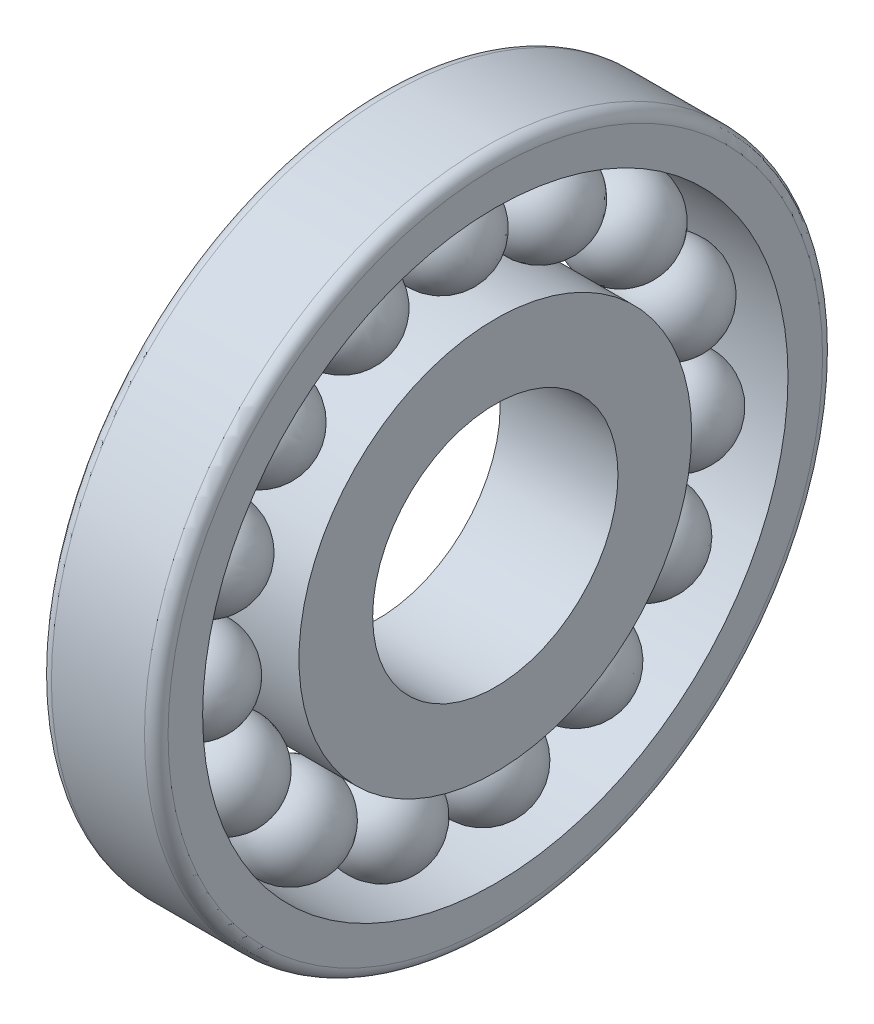
SolidWorks part; units mm, degrees
ref_plane "Front Plane" through (0, 0, 0) normal (0, 0, 1) x (1, 0, 0)
ref_plane "Top Plane" through (0, 0, 0) normal (0, 1, 0) x (1, 0, 0)
ref_plane "Right Plane" through (0, 0, 0) normal (1, 0, 0) x (0, 0, -1)
sketch "Sketch1" plane through (0, 0, 0) normal (1, 0, 0) x (0, 0, -1)
  circle A1 centre (0, 0) radius 42.3268
  circle A2 centre (0, 0) radius 26.4428
extrude "Boss-Extrude1" add sketch "Sketch1" along normal blind 25.4
ref_plane "Plane1" through (12.7, 0, 0) normal (1, 0, 0) x (0, 0, -1)
sketch "Sketch7" plane through (12.7, 0, 0) normal (1, 0, 0) x (0, 0, -1)
  line L0 (31.093, 40.1502) -> (48.0404, 28.5061)
  arc A0 (31.093, 40.1502) -> (48.0404, 28.5061) centre (39.5667, 34.3281) ccw
revolve "Revolve4" add sketch "Sketch7" angle 360 about L0
pattern_circular "CirPattern2" count 15 every 24 about axis through (0, 0, 0) along (1, 0, 0) of "Revolve4"
sketch "Sketch9" plane through (25.4, 0, 0) normal (1, 0, 0) x (0, 0, -1)
  circle A0 centre (0, 0) radius 63.1037
  circle A1 centre (0, 0) radius 73.0966
extrude "Boss-Extrude2" add sketch "Sketch9" against normal blind 25.146 separate body
fillet "Fillet2" radius 2.54 2 edges at (0.254, 0, -73.0966) (25.4, 0, -73.0966)
ref_plane "Plane2" through (2.54, 0, 0) normal (1, 0, 0) x (0, 0, -1)
